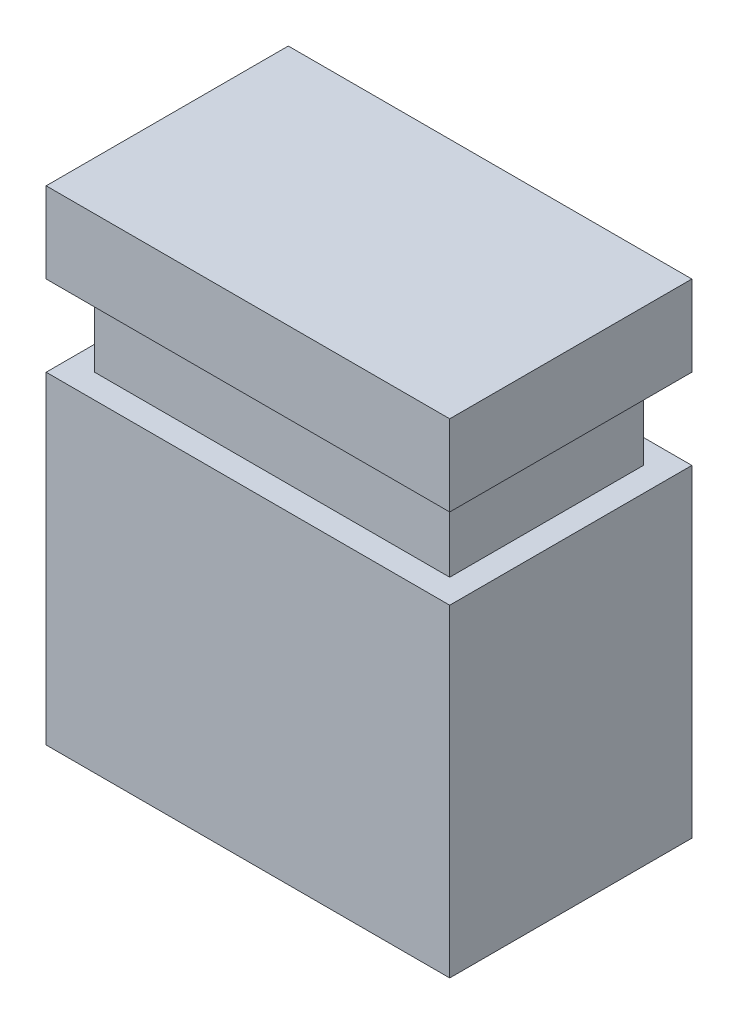
SolidWorks part; units mm, degrees
ref_plane "Front Plane" through (0, 0, 0) normal (0, 0, 1) x (1, 0, 0)
ref_plane "Top Plane" through (0, 0, 0) normal (0, 1, 0) x (1, 0, 0)
ref_plane "Right Plane" through (0, 0, 0) normal (1, 0, 0) x (0, 0, -1)
sketch "Sketch1" plane through (0, 0, 0) normal (0, 1, 0) x (1, 0, 0)
  line L1 (-1.25, 0.75) -> (1.25, 0.75)
  line L2 (-1.25, 0.75) -> (-1.25, -0.75)
  line L3 (-1.25, -0.75) -> (1.25, -0.75)
  line L4 (1.25, 0.75) -> (1.25, -0.75)
  line L5 (-1.25, 0.75) -> (1.25, -0.75) construction
  line L6 (-1.25, -0.75) -> (1.25, 0.75) construction
  point P0 (0, 0)
  dimension "D1" = 2.5
  dimension "D2" = 1.5
extrude "Boss-Extrude1" add sketch "Sketch1" along normal blind 2
sketch "Sketch2" plane through (0, 2, 0) normal (0, 1, 0) x (1, 0, 0)
  line L0 (1.25, 0.75) -> (-1.25, 0.75) construction
  line L1 (1.1, 0.6) -> (-1.1, 0.6)
  line L2 (1.1, 0.6) -> (1.1, -0.6)
  line L3 (1.1, -0.6) -> (-1.1, -0.6)
  line L4 (-1.1, 0.6) -> (-1.1, -0.6)
  line L5 (1.1, 0.6) -> (-1.1, -0.6) construction
  line L6 (1.1, -0.6) -> (-1.1, 0.6) construction
  line L7 (1.25, -0.75) -> (1.25, 0.75) construction
  point P0 (0, 0)
  dimension "D1" = 0.15
  dimension "D2" = 0.15
extrude "Boss-Extrude2" add sketch "Sketch2" along normal blind 0.5
sketch "Sketch3" plane through (0, 2.5, 0) normal (0, 1, 0) x (1, 0, 0)
  line L1 (-1.25, 0.75) -> (1.25, 0.75)
  line L2 (-1.25, 0.75) -> (-1.25, -0.75)
  line L3 (-1.25, -0.75) -> (1.25, -0.75)
  line L4 (1.25, 0.75) -> (1.25, -0.75)
extrude "Boss-Extrude3" add sketch "Sketch3" along normal blind 0.5
sketch "Sketch5" plane through (0, 0, 0) normal (0, -1, 0) x (1, 0, 0)
  line L0 (1.25, 0.75) -> (1.25, -0.75) construction
  line L1 (1, 0.5) -> (-1, 0.5)
  line L2 (1, 0.5) -> (1, -0.5)
  line L3 (1, -0.5) -> (-1, -0.5)
  line L4 (-1, 0.5) -> (-1, -0.5)
  line L5 (1, 0.5) -> (-1, -0.5) construction
  line L6 (1, -0.5) -> (-1, 0.5) construction
  line L7 (-1.25, 0.75) -> (1.25, 0.75) construction
  point P0 (0, 0)
  dimension "D1" = 0.25
  dimension "D2" = 0.25
extrude "Cut-Extrude1" cut sketch "Sketch5" against normal blind 0.2
sketch "Sketch6" plane through (0, 0.2, 0) normal (0, -1, 0) x (1, 0, 0)
  line L0 (-1.25, 0) -> (1.25, 0) construction
  line L1 (-1.25, -0.75) -> (-1.25, 0.75) construction
  line L2 (1.25, 0.75) -> (1.25, -0.75) construction
  line L3 (0, 0.75) -> (0, -0.75) construction
  line L4 (-0.885, 0.25) -> (-0.385, 0.25)
  line L5 (-0.885, 0.25) -> (-0.885, -0.25)
  line L6 (-0.885, -0.25) -> (-0.385, -0.25)
  line L7 (-0.385, 0.25) -> (-0.385, -0.25)
  line L8 (-0.885, 0.25) -> (-0.385, -0.25) construction
  line L9 (-0.885, -0.25) -> (-0.385, 0.25) construction
  line L10 (-1.25, 0.75) -> (1.25, 0.75) construction
  line L11 (1.25, -0.75) -> (-1.25, -0.75) construction
  line L12 (0.385, 0.25) -> (0.385, -0.25)
  line L13 (0.885, -0.25) -> (0.385, -0.25)
  line L14 (0.885, 0.25) -> (0.885, -0.25)
  line L15 (0.885, 0.25) -> (0.385, 0.25)
  point P6 (-0.635, 0)
  dimension "D1" = 0.5
  dimension "D2" = 1.27
extrude "Cut-Extrude2" cut sketch "Sketch6" against normal offset from surface (2.3 mm away) 0.5 up to face at (0, 3, 0)
